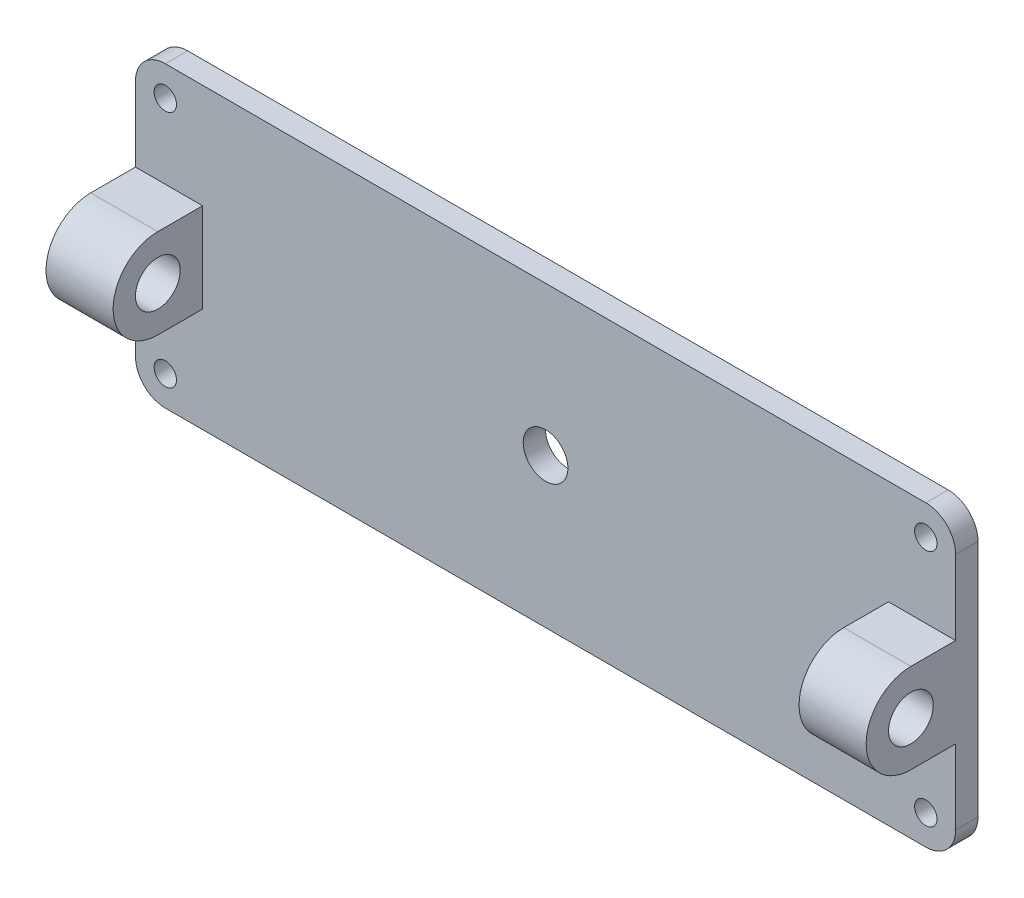
SolidWorks part; units mm, degrees
ref_plane "Front Plane" through (0, 0, 0) normal (0, 0, 1) x (1, 0, 0)
ref_plane "Top Plane" through (0, 0, 0) normal (0, 1, 0) x (1, 0, 0)
ref_plane "Right Plane" through (0, 0, 0) normal (1, 0, 0) x (0, 0, -1)
sketch "Sketch1" plane through (0, 0, 0) normal (0, 0, 1) x (1, 0, 0)
  line L1 (-349.25, -127) -> (349.25, -127)
  line L2 (-349.25, -127) -> (-349.25, 127)
  line L3 (-349.25, 127) -> (349.25, 127)
  line L4 (349.25, -127) -> (349.25, 127)
  line L5 (-349.25, -127) -> (349.25, 127) construction
  line L6 (-349.25, 127) -> (349.25, -127) construction
  circle A0 centre (0, 0) radius 19.05
  circle A1 centre (-323.85, 101.6) radius 9.525
  circle A2 centre (323.85, 101.6) radius 9.525
  circle A3 centre (323.85, -101.6) radius 9.525
  circle A4 centre (-323.85, -101.6) radius 9.525
  point P0 (0, 0)
  dimension "D3" = 38.1
  dimension "D4" = 19.05
  dimension "D1" = 698.5
  dimension "D2" = 254
  dimension "D5" = 25.4
  dimension "D6" = 25.4
  dimension "D7" = 2
  dimension "D8" = 2
extrude "Boss-Extrude1" add sketch "Sketch1" along normal blind 19.05
fillet "Fillet3" radius 25.4 1 edges at (-349.25, 127, 9.525)
fillet "Fillet4" radius 25.4 1 edges at (-349.25, -127, 9.525)
fillet "Fillet5" radius 25.4 1 edges at (349.25, -127, 9.525)
fillet "Fillet6" radius 25.4 1 edges at (349.25, 127, 9.525)
ref_plane "Plane1" through (349.25, 0, 0) normal (1, 0, 0) x (0, 0, -1)
sketch "Sketch2" plane through (349.25, 0, 0) normal (1, 0, 0) x (0, 0, -1)
  line L0 (-19.05, 101.6) -> (-19.05, -101.6) construction
  line L2 (-19.05, 38.1) -> (-19.05, -38.1)
  line L3 (-19.05, -38.1) -> (-57.15, -38.1)
  line L5 (0, -101.6) -> (0, 101.6) construction
  line L6 (-19.05, 38.1) -> (-57.15, 38.1)
  arc A0 (-57.15, -38.1) -> (-57.15, 38.1) centre (-57.15, 0) cw
  circle A1 centre (-57.15, 0) radius 19.05
  dimension "D1" = 38.1
  dimension "D3" = 38.1
  dimension "D2" = 57.15
extrude "Boss-Extrude2" add sketch "Sketch2" against normal blind 57.15 contours L2 L3 A0 L6 | A1
ref_plane "Plane2" through (0, 0, 0) normal (-1, 0, 0) x (0, 0, 1)
mirror "Mirror3" about plane through (0, 0, 0) normal (-1, 0, 0) of "Boss-Extrude2"
